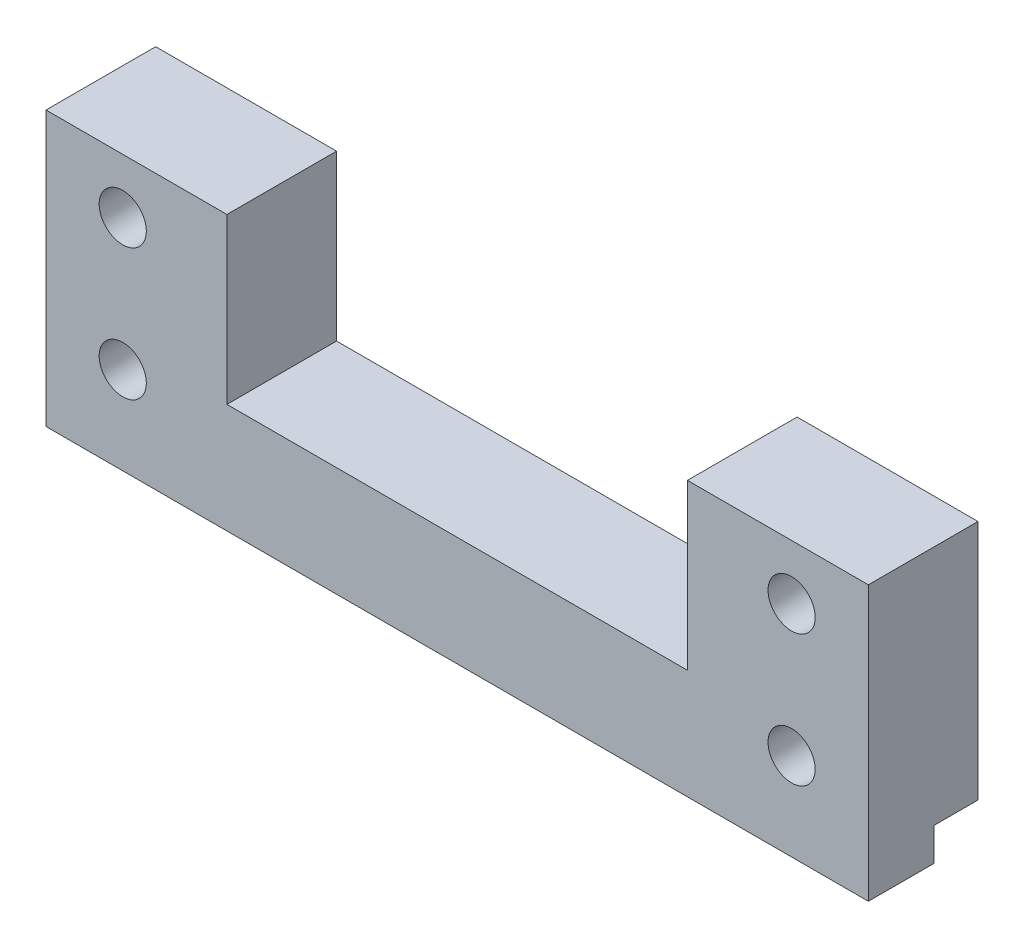
SolidWorks part; units mm, degrees
ref_plane "Front Plane" through (0, 0, 0) normal (0, 0, 1) x (1, 0, 0)
ref_plane "Top Plane" through (0, 0, 0) normal (0, 1, 0) x (1, 0, 0)
ref_plane "Right Plane" through (0, 0, 0) normal (1, 0, 0) x (0, 0, -1)
sketch "Sketch1" plane through (0, 0, 0) normal (0, 0, 1) x (1, 0, 0)
  line L0 (21, 5) -> (37.5, 5)
  line L1 (-37.5, 5) -> (-21, 5)
  line L2 (-37.5, 5) -> (-37.5, -20)
  line L3 (-37.5, -20) -> (37.5, -20)
  line L4 (37.5, 5) -> (37.5, -20)
  line L5 (-21, 5) -> (21, 5) construction
  line L6 (-21, 5) -> (-21, -10)
  line L7 (-21, -10) -> (21, -10)
  line L8 (21, 5) -> (21, -10)
  line L9 (30.5, -12) -> (30.5, 0) construction
  line L10 (30.5, 0) -> (-30.5, 0) construction
  line L11 (-30.5, 0) -> (-30.5, -12) construction
  line L12 (-30.5, -12) -> (30.5, -12) construction
  line L13 (-30.5, 0) -> (30.5, -12) construction
  line L14 (0, -10) -> (0, 0) construction
  circle A0 centre (-30.5, 0) radius 2.15
  circle A1 centre (-30.5, -12) radius 2.15
  circle A2 centre (30.5, 0) radius 2.15
  circle A3 centre (30.5, -12) radius 2.15
  dimension "D3" = 4.3
  dimension "D1" = 61
  dimension "D2" = 12
  dimension "D4" = 5
  dimension "D5" = 75
  dimension "D6" = 42
  dimension "D7" = 10
  dimension "D8" = 10
extrude "Boss-Extrude1" add sketch "Sketch1" along normal blind 10
sketch "Sketch3" plane through (0, 0, 0) normal (0, 0, -1) x (-1, 0, 0)
  line L0 (37.5, 5) -> (37.5, -20) construction
  line L1 (-37.5, -20) -> (37.5, -20)
  line L2 (-37.5, -20) -> (-37.5, -17)
  line L3 (-37.5, -17) -> (37.5, -17)
  line L4 (37.5, -20) -> (37.5, -17)
  circle A0 centre (30.5, -12) radius 2.15 construction
  dimension "D1" = 5
extrude "Cut-Extrude1" cut sketch "Sketch3" against normal blind 4
